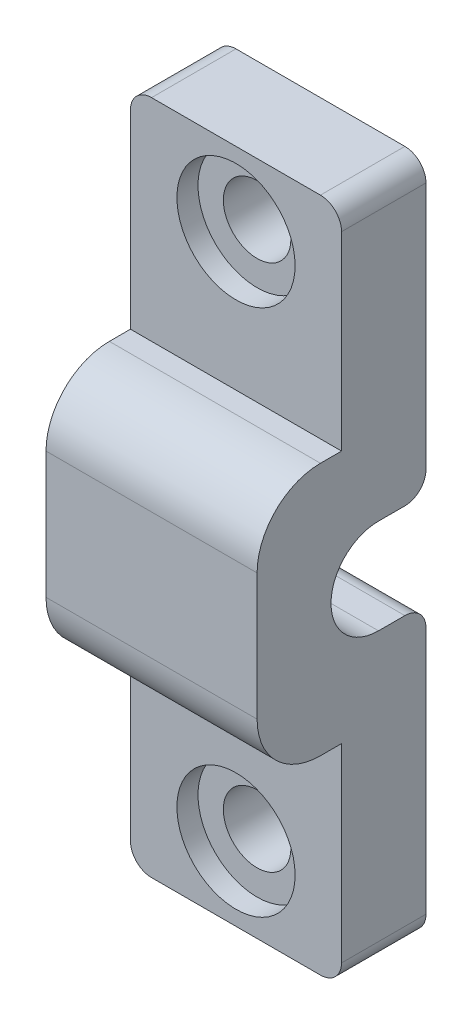
SolidWorks part; units mm, degrees
ref_plane "Alzado" through (0, 0, 0) normal (0, 0, 1) x (1, 0, 0)
ref_plane "Planta" through (0, 0, 0) normal (0, 1, 0) x (1, 0, 0)
ref_plane "Vista lateral" through (0, 0, 0) normal (1, 0, 0) x (0, 0, -1)
sketch "Croquis1" plane through (0, 0, 0) normal (0, 0, 1) x (1, 0, 0)
  line L1 (0, 0) -> (10, 0)
  line L2 (0, 0) -> (0, 32)
  line L3 (0, 32) -> (10, 32)
  line L4 (10, 0) -> (10, 32)
  dimension "D1" = 10
  dimension "D2" = 32
extrude "Saliente-Extruir1" add sketch "Croquis1" along normal blind 8
sketch "Croquis2" plane through (0, 0, 8) normal (0, 0, 1) x (1, 0, 0)
  line L0 (5, 32) -> (5, 0) construction
  line L1 (10, 32) -> (0, 32) construction
  line L2 (0, 0) -> (10, 0) construction
  circle A0 centre (5, 28.5) radius 1.6
  circle A1 centre (5, 3.5) radius 1.6
  dimension "D1" = 3.2
  dimension "D2" = 3.2
  dimension "D3" = 25
  dimension "D4" = 3.5
extrude "Cortar-Extruir1" cut sketch "Croquis2" against normal up to surface (8 mm away) up to face at (5, 16, 0)
sketch "Croquis3" plane through (0, 0, 0) normal (-1, 0, 0) x (0, 0, 1)
  line L6 (0, 32) -> (0, 0) construction
  line L7 (8, 32) -> (0, 32) construction
  line L8 (2.25, 18.25) -> (0, 18.25)
  line L9 (2.25, 13.75) -> (0, 13.75)
  line L10 (0, 13.75) -> (0, 18.25)
  circle A0 centre (2.25, 16) radius 2.25
  line M2 (0, 32) -> (0, 0)
  dimension "D2" = 4.5
  dimension "D1" = 16
extrude "Cortar-Extruir2" cut sketch "Croquis3" against normal up to surface (10 mm away) contours A0 | A0 L8 M2 | A0 L10 L9 up to face at (10, 16, 4)
fillet "Redondeo1" radius 1 2 edges at (5, 13.75, 0) (5, 18.25, 0)
sketch "Croquis4" plane through (0, 0, 0) normal (-1, 0, 0) x (0, 0, 1)
  line L1 (8, 32) -> (4, 32)
  line L2 (8, 32) -> (8, 22)
  line L3 (8, 22) -> (4, 22)
  line L4 (4, 32) -> (4, 22)
  line L5 (8, 0) -> (4, 0)
  line L6 (8, 0) -> (8, 10)
  line L7 (8, 10) -> (4, 10)
  line L8 (4, 0) -> (4, 10)
  dimension "D1" = 4
  dimension "D2" = 4
  dimension "D3" = 10
  dimension "D4" = 10
extrude "Cortar-Extruir3" cut sketch "Croquis4" against normal up to surface (10 mm away)
fillet "Redondeo2" radius 3 2 edges at (5, 10, 8) (5, 22, 8)
fillet "Redondeo3" radius 1 4 edges at (10, 32, 2) (0, 32, 2) (0, 0, 2) (10, 0, 2)
sketch "Croquis5" plane through (0, 0, 4) normal (0, 0, 1) x (1, 0, 0)
  circle A0 centre (5, 28.5) radius 2.8
  circle A1 centre (5, 3.5) radius 2.8
  dimension "D1" = 5.6
extrude "Cortar-Extruir4" cut sketch "Croquis5" against normal blind 1
